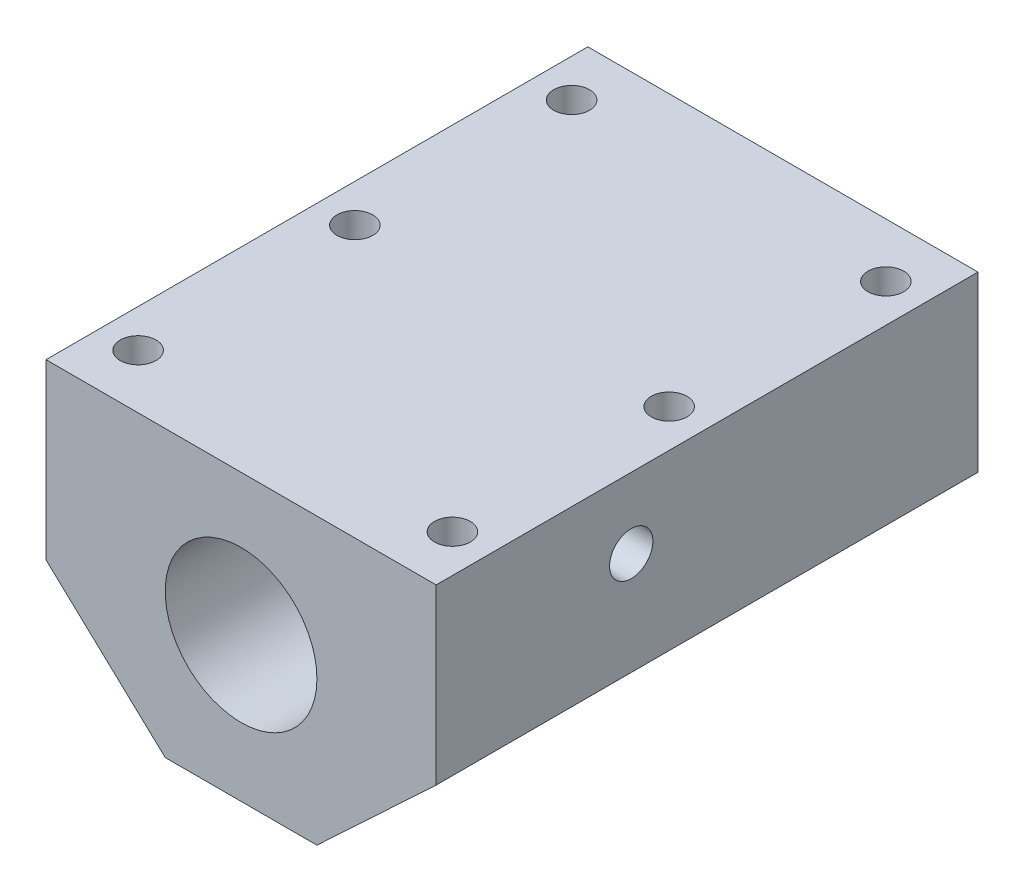
SolidWorks part; units mm, degrees
ref_plane "前视基准面" through (0, 0, 0) normal (0, 0, 1) x (1, 0, 0)
ref_plane "上视基准面" through (0, 0, 0) normal (0, 1, 0) x (1, 0, 0)
ref_plane "右视基准面" through (0, 0, 0) normal (1, 0, 0) x (0, 0, -1)
sketch "草图1" plane through (0, 0, 0) normal (0, 0, 1) x (1, 0, 0)
  line L1 (-14, 0) -> (14, 0) construction
  line L2 (0, -55.6107) -> (0, 55.6107) construction
  line L3 (-18, 13) -> (-18, -3)
  line L4 (7, -13.3) -> (-7, -13.3)
  line L5 (-18, -3) -> (-7, -13.3)
  line L6 (18, -3) -> (7, -13.3)
  line L7 (18, 13) -> (18, -3)
  line L29 (-18, 13) -> (18, 13)
  point P10 (0, 0)
  point P11 (0, -13.3)
  point P36 (0, 13)
  dimension "D2" = 5
  dimension "D3" = 14
  dimension "D4" = 36
  dimension "D19" = 26.3
extrude "拉伸1" add sketch "草图1" along normal blind 50
sketch "草图2" plane through (0, 0, 50) normal (0, 0, 1) x (1, 0, 0)
  line L0 (0, -13.3) -> (0, 13) construction
  line L30 (18, -3) -> (18, 13)
  line L31 (18, -3) -> (18, 13)
  line L33 (-18, 13) -> (-18, -3)
  line L34 (-18, -3) -> (-7, -13.3)
  line L35 (-7, -13.3) -> (7, -13.3)
  line L36 (7, -13.3) -> (18, -3)
  line L51 (18, 13) -> (-18, 13)
  line L65 (-18, 13) -> (-18, -3)
  line L66 (-18, -3) -> (-7, -13.3)
  line L67 (-7, -13.3) -> (7, -13.3)
  line L68 (7, -13.3) -> (18, -3)
  line L83 (18, 13) -> (-18, 13)
  circle A0 centre (0, 0) radius 7
  dimension "D2" = 14
  dimension "D1" = 0
extrude "拉伸3" cut sketch "草图2" against normal blind 10 flip side to cut
sketch "草图5" plane through (0, 0, 40) normal (0, 0, 1) x (1, 0, 0)
  circle A0 centre (0, 0) radius 11
  dimension "D1" = 22
extrude "拉伸5" cut sketch "草图5" against normal blind 27
hole_wizard "M24 螺纹孔1" positions "3D草图16" profile "草图57" tap size "M24" standard "GB"
sketch3d "3D草图16"
  point P0 (0, 0, 0)
  point P3 (0, 0, 13)
sketch "草图57" plane through (0, 0, 13) normal (1, 0, 0) x (0, -1, 0)
  line L0 (0, 0) -> (0, 19.9099)
  line L1 (0, 19.9099) -> (11.5, 13)
  line L2 (11.5, 13) -> (11.5, 0)
  line L5 (11.5, 0) -> (0, 0)
  line L10 (0, 19.9099) -> (-11.5, 13) construction
  line L11 (0, -6.35) -> (0, 107.95) construction
  dimension "螺纹孔钻头直径" = 23
  dimension "螺纹孔钻头深度" = 13
  dimension "导头角度" = 118
cosmetic thread "孔螺蚊线26" parameters "D1"=8, "D2"=24
cosmetic thread "孔螺蚊线27" parameters "D1"=8, "D2"=24
hole_wizard "M4 螺纹孔1" positions "草图60" profile "草图58" tap size "M4" standard "GB"
sketch "草图60" plane through (0, 13, 0) normal (0, 1, 0) x (1, 0, 0)
  line L0 (0, 0) -> (0, -50) construction
  line L1 (18, -50) -> (-18, -50) construction
  line L3 (-18, -25) -> (18, -25) construction
  line L4 (-18, -50) -> (-18, 0) construction
  line L5 (18, -50) -> (18, 0) construction
  point P0 (-14.5, -5)
  point P2 (-14.5, -25)
  point P4 (-14.5, -45)
  dimension "D1" = 40
  dimension "D2" = 29
sketch "草图58" plane through (-14.5, 13, 5) normal (1, 0, 0) x (0, 0, 1)
  line L0 (0, 0) -> (0, 12.4914)
  line L1 (0, 12.4914) -> (1.65, 11.5)
  line L2 (1.65, 11.5) -> (1.65, 0)
  line L5 (1.65, 0) -> (0, 0)
  line L10 (0, 12.4914) -> (-1.65, 11.5) construction
  line L11 (0, -6.35) -> (0, 107.95) construction
  dimension "螺纹孔钻头直径" = 3.3
  dimension "螺纹孔钻头深度" = 11.5
  dimension "导头角度" = 118
cosmetic thread "孔螺蚊线28" parameters "D1"=8, "D2"=4
cosmetic thread "孔螺蚊线29" parameters "D1"=8, "D2"=4
cosmetic thread "孔螺蚊线30" parameters "D1"=8, "D2"=4
mirror "镜向1" about plane through (0, 0, 0) normal (1, 0, 0) of "M4 螺纹孔1"
sketch "草图61" plane through (0, 0, 0) normal (0, 0, -1) x (-1, 0, 0)
  line L0 (-10.4851, 7.3418) -> (0, 0) construction
  line L1 (-9.338, 8.9801) -> (1.1472, 1.6383)
  line L2 (-11.6323, 5.7035) -> (-1.1472, -1.6383)
  line L3 (0, 11) -> (0, 0) construction
  arc A0 (-9.338, 8.9801) -> (-11.6323, 5.7035) centre (-10.4851, 7.3418) ccw
  arc A1 (-1.1472, -1.6383) -> (1.1472, 1.6383) centre (0, 0) ccw
  circle A2 centre (0, 0) radius 11 construction
  circle A3 centre (0, 0) radius 11 construction
  point P2 (-5.2426, 3.6709)
  dimension "D1" = 2
  dimension "D2" = 12.8
  dimension "D3" = 55
extrude "切除-拉伸1" cut sketch "草图61" against normal blind 34
hole_wizard "Ø3.0 (3) 直径孔1" positions "草图63" profile "草图64" hole size "Ø3.0" standard "GB"
sketch "草图63" plane through (18, 0, 0) normal (1, 0, 0) x (0, 0, -1)
  line L0 (0, -3) -> (0, 13) construction
  line L1 (-50, 13) -> (0, 13) construction
  point P0 (-32, 6.5)
  dimension "D1" = 32
  dimension "D2" = 6.5
sketch "草图64" plane through (18, 6.5, 32) normal (0, 1, 0) x (0, 0, -1)
  line L0 (0, 0) -> (0, 5.7006)
  line L1 (0, 5.7006) -> (1.5, 5.7006)
  line L2 (1.5, 5.7006) -> (1.5, 0)
  line L5 (1.5, 0) -> (0, 0)
  line L11 (0, -6.35) -> (0, 107.95) construction
  dimension "通孔孔直径" = 3
  dimension "通孔孔深度" = 5.7006
sketch "草图65" plane through (18, 0, 0) normal (1, 0, 0) x (0, 0, -1)
  circle A0 centre (-32, 6.5) radius 2
  dimension "D1" = 4
extrude "切除-拉伸2" cut sketch "草图65" against normal blind 5
